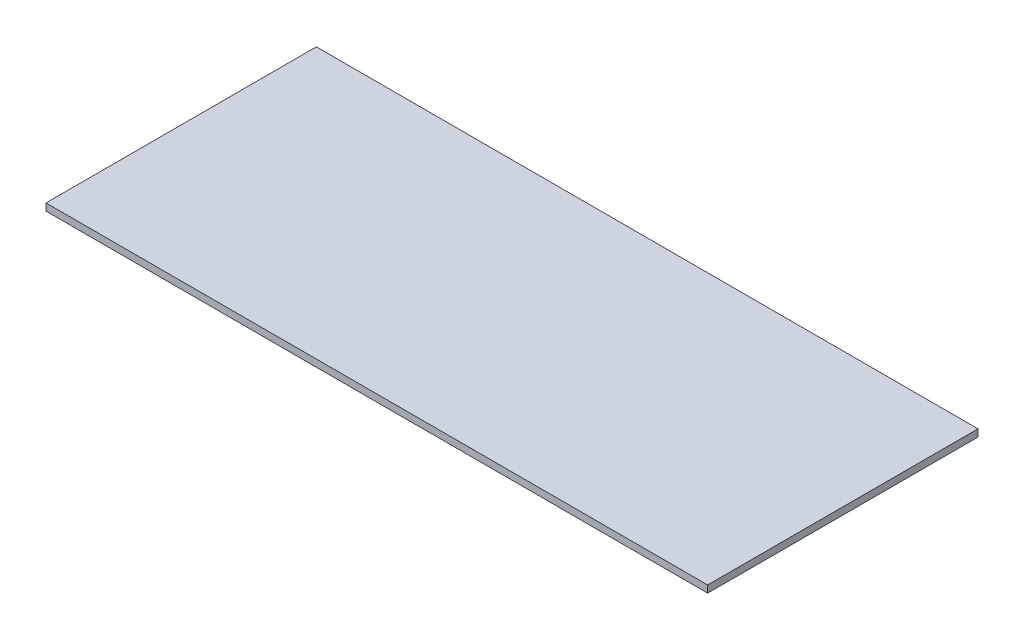
SolidWorks part; units mm, degrees
ref_plane "Front Plane" through (0, 0, 0) normal (0, 0, 1) x (1, 0, 0)
ref_plane "Top Plane" through (0, 0, 0) normal (0, 1, 0) x (1, 0, 0)
ref_plane "Right Plane" through (0, 0, 0) normal (1, 0, 0) x (0, 0, -1)
sketch "Sketch1" plane through (0, 0, 0) normal (0, 1, 0) x (1, 0, 0)
  line L1 (-75.8893, 18.2309) -> (42.2207, 18.2309)
  line L2 (-75.8893, 18.2309) -> (-75.8893, -30.0291)
  line L3 (-75.8893, -30.0291) -> (42.2207, -30.0291)
  line L4 (42.2207, 18.2309) -> (42.2207, -30.0291)
extrude "Boss-Extrude1" add sketch "Sketch1" along normal blind 1.27
